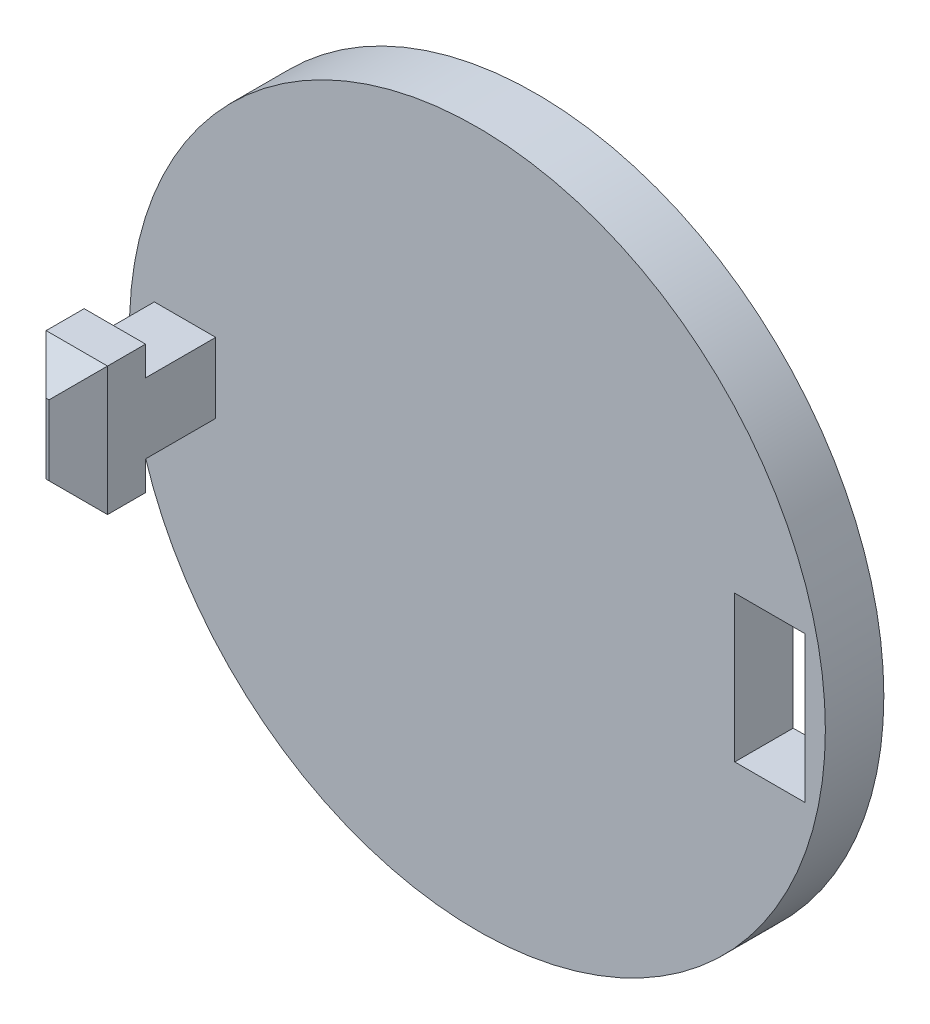
SolidWorks part; units mm, degrees
material "ABS PC"
ref_plane "Front Plane" through (0, 0, 0) normal (0, 0, 1) x (1, 0, 0)
ref_plane "Top Plane" through (0, 0, 0) normal (0, 1, 0) x (1, 0, 0)
ref_plane "Right Plane" through (0, 0, 0) normal (1, 0, 0) x (0, 0, -1)
sketch "Sketch1" plane through (0, 0, 0) normal (0, 0, 1) x (1, 0, 0)
  line L0 (0, 0) -> (0, 6.3935) construction
  line L1 (0, 6.3935) -> (0, 0) construction
  line L2 (0, 0) -> (10, 0) construction
  line L4 (8.8, 2.5) -> (11.2, 2.5)
  line L5 (8.8, 2.5) -> (8.8, -2.5)
  line L6 (8.8, -2.5) -> (11.2, -2.5)
  line L7 (11.2, 2.5) -> (11.2, -2.5)
  line L8 (8.8, 2.5) -> (11.2, -2.5) construction
  line L9 (8.8, -2.5) -> (11.2, 2.5) construction
  circle A0 centre (0, 0) radius 11.9
  dimension "D1" = 10
  dimension "D4" = 23.8
  dimension "D2" = 5
  dimension "D3" = 2.4
extrude "Boss-Extrude2" add sketch "Sketch1" along normal blind 2
sketch "Sketch2" plane through (0, 0, 2) normal (0, 0, 1) x (1, 0, 0)
  line L0 (0, 0) -> (-10, 0) construction
  line L1 (-10, 0) -> (-10, -1.2) construction
  line L7 (-11.15, -2.4) -> (-8.85, 0) construction
  line L8 (-11.1407, 0.0914) -> (-8.94, -2.4) construction
  line L9 (-11.05, 1.2) -> (-8.95, 1.2)
  line L10 (-11.05, 1.2) -> (-11.05, -1.2)
  line L11 (-11.05, -1.2) -> (-8.95, -1.2)
  line L12 (-8.95, 1.2) -> (-8.95, -1.2)
  line L13 (-11.05, 1.2) -> (-8.95, -1.2) construction
  line L14 (-11.05, -1.2) -> (-8.95, 1.2) construction
  dimension "D1" = 10
  dimension "D2" = 1.2
  dimension "D3" = 2.21
  dimension "D4" = 2.1
  dimension "D5" = 2.4
extrude "Boss-Extrude3" add sketch "Sketch2" along normal blind 4.7
sketch "Sketch4" plane through (0, 1.2, 0) normal (0, 1, 0) x (1, 0, 0)
  line L0 (-11.05, -6.7) -> (-11.05, -2) construction
  line L1 (-8.95, -6.7) -> (-11.05, -6.7)
  line L2 (-8.95, -6.7) -> (-8.95, -4.4)
  line L3 (-8.95, -4.4) -> (-11.05, -4.4)
  line L4 (-11.05, -6.7) -> (-11.05, -4.4)
  dimension "D1" = 2.3
extrude "Boss-Extrude5" add sketch "Sketch4" along normal blind 1
sketch "Sketch5" plane through (0, -1.2, 0) normal (0, -1, 0) x (1, 0, 0)
  line L0 (-8.95, 6.7) -> (-8.95, 2) construction
  line L1 (-11.05, 6.7) -> (-8.95, 6.7)
  line L2 (-11.05, 6.7) -> (-11.05, 4.4)
  line L3 (-11.05, 4.4) -> (-8.95, 4.4)
  line L4 (-8.95, 6.7) -> (-8.95, 4.4)
  dimension "D1" = 2.3
extrude "Boss-Extrude6" add sketch "Sketch5" along normal blind 1
chamfer "Chamfer1" distance 1 angle 45 4 edges at (-10, -2.2, 6.7) (-11.05, 0, 6.7) (-10, 2.2, 6.7) (-8.95, 0, 6.7)
